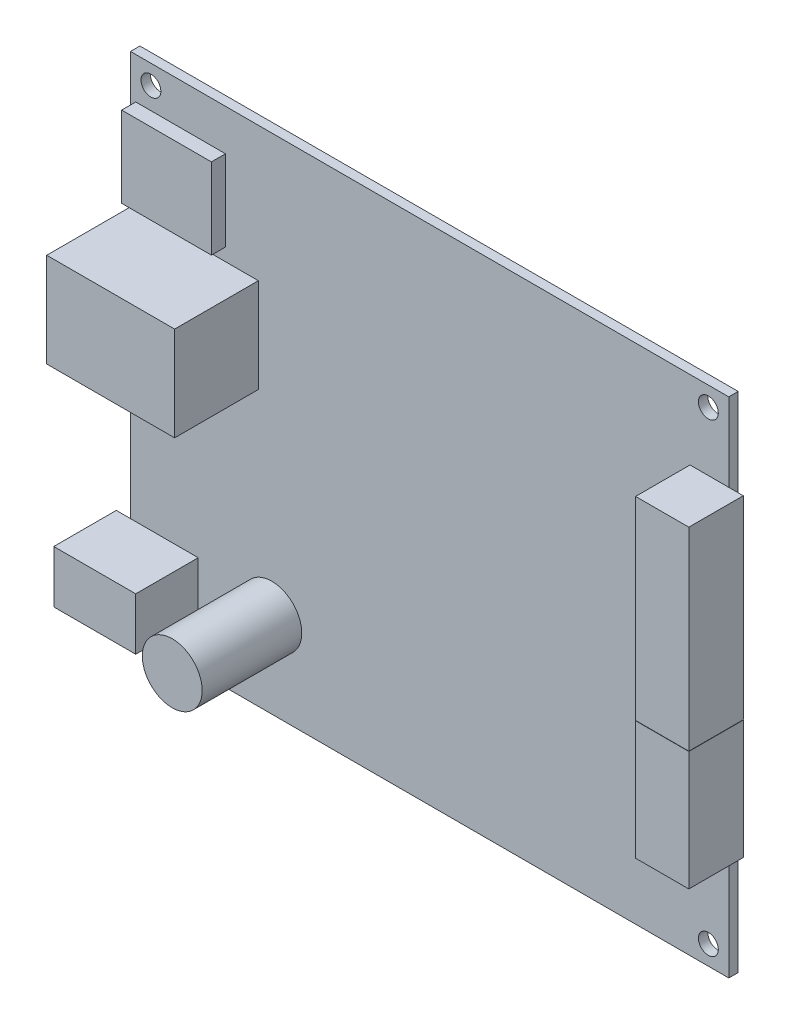
SolidWorks part; units mm, degrees
ref_plane "Front Plane" through (0, 0, 0) normal (0, 0, 1) x (1, 0, 0)
ref_plane "Top Plane" through (0, 0, 0) normal (0, 1, 0) x (1, 0, 0)
ref_plane "Right Plane" through (0, 0, 0) normal (1, 0, 0) x (0, 0, -1)
sketch "Sketch1" plane through (0, 0, 0) normal (0, 0, 1) x (1, 0, 0)
  line L1 (-50.8, -42.7355) -> (50.8, -42.7355)
  line L2 (-50.8, -42.7355) -> (-50.8, 42.7355)
  line L3 (-50.8, 42.7355) -> (50.8, 42.7355)
  line L4 (50.8, -42.7355) -> (50.8, 42.7355)
  line L5 (-50.8, -42.7355) -> (50.8, 42.7355) construction
  line L6 (-50.8, 42.7355) -> (50.8, -42.7355) construction
  point P0 (0, 0)
  dimension "D1" = 101.6
  dimension "D2" = 85.471
extrude "Boss-Extrude1" add sketch "Sketch1" along normal blind 1.6002
sketch "Sketch2" plane through (0, 0, 1.6002) normal (0, 0, 1) x (1, 0, 0)
  line L0 (-50.8, 42.7355) -> (-50.8, -42.7355) construction
  line L1 (-50.8, 3.8735) -> (-29.083, 3.8735)
  line L2 (-50.8, 3.8735) -> (-50.8, 19.8755)
  line L3 (-50.8, 19.8755) -> (-29.083, 19.8755)
  line L4 (-29.083, 3.8735) -> (-29.083, 19.8755)
  line L5 (50.8, 42.7355) -> (-50.8, 42.7355) construction
  dimension "D1" = 16.002
  dimension "D2" = 21.717
  dimension "D3" = 22.86
extrude "Ethernet" add sketch "Sketch2" along normal blind 14.224
sketch "Sketch3" plane through (0, 0, 1.6002) normal (0, 0, 1) x (1, 0, 0)
  line L1 (-53.213, -34.8615) -> (-39.2938, -34.8615)
  line L2 (-53.213, -34.8615) -> (-53.213, -25.9715)
  line L3 (-53.213, -25.9715) -> (-39.2938, -25.9715)
  line L4 (-39.2938, -34.8615) -> (-39.2938, -25.9715)
  line L5 (-50.8, -42.7355) -> (50.8, -42.7355) construction
  line L6 (-50.8, 3.8735) -> (-50.8, -42.7355) construction
  dimension "D1" = 8.89
  dimension "D2" = 13.9192
  dimension "D3" = 7.874
  dimension "D4" = 2.413
extrude "Power Connector" add sketch "Sketch3" along normal blind 10.6172
sketch "Sketch4" plane through (0, 0, 1.6002) normal (0, 0, 1) x (1, 0, 0)
  line L0 (50.8, 42.7355) -> (-50.8, 42.7355) construction
  line L1 (53.2638, 29.4259) -> (44.2214, 29.4259)
  line L2 (53.2638, 29.4259) -> (53.2638, -3.5179)
  line L3 (53.2638, -3.5179) -> (44.2214, -3.5179)
  line L4 (44.2214, 29.4259) -> (44.2214, -3.5179)
  line L5 (53.2638, -3.5687) -> (44.2214, -3.5687)
  line L6 (53.2638, -3.5687) -> (53.2638, -23.7871)
  line L7 (53.2638, -23.7871) -> (44.2214, -23.7871)
  line L8 (44.2214, -3.5687) -> (44.2214, -23.7871)
  line L9 (50.8, -42.7355) -> (50.8, 42.7355) construction
  dimension "D1" = 0.0508
  dimension "D2" = 9.0424
  dimension "D3" = 32.9438
  dimension "D4" = 20.2184
  dimension "D5" = 13.3096
  dimension "D6" = 2.4638
extrude "2x Connector" add sketch "Sketch4" along normal blind 9.2456
sketch "Sketch6" plane through (0, 0, 1.6002) normal (0, 0, 1) x (1, 0, 0)
  line L0 (-50.8, 42.7355) -> (-50.8, 19.8755) construction
  line L1 (-49.911, 22.0345) -> (-34.671, 22.0345)
  line L2 (-49.911, 22.0345) -> (-49.911, 35.7505)
  line L3 (-49.911, 35.7505) -> (-34.671, 35.7505)
  line L4 (-34.671, 22.0345) -> (-34.671, 35.7505)
  line L5 (50.8, 42.7355) -> (-50.8, 42.7355) construction
  dimension "D1" = 13.716
  dimension "D2" = 15.24
  dimension "D3" = 0.889
  dimension "D4" = 6.985
extrude "SD Card" add sketch "Sketch6" along normal blind 2.3876
sketch "Sketch7" plane through (0, 0, 1.6002) normal (0, 0, 1) x (1, 0, 0)
  line L0 (-50.8, -42.7355) -> (50.8, -42.7355) construction
  line L2 (50.8, -42.7355) -> (50.8, -23.7871) construction
  circle A0 centre (-26.797, -28.2575) radius 5.08
  dimension "D1" = 10.16
  dimension "D2" = 14.478
  dimension "D3" = 77.597
extrude "Capacator" add sketch "Sketch7" along normal blind 16.9164
sketch "Sketch5" plane through (0, 0, 0) normal (0, 0, -1) x (-1, 0, 0)
  line L0 (-50.8, -42.7355) -> (-50.8, 42.7355) construction
  line L1 (-50.8, 42.7355) -> (50.8, 42.7355) construction
  circle A0 centre (-47.3329, 39.4462) radius 1.6891
  dimension "D1" = 3.3782
  dimension "D2" = 3.4671
  dimension "D3" = 3.2893
extrude "Corner Hole" cut sketch "Sketch5" against normal through all
mirror "Mirror1" about plane through (0, 0, 0) normal (1, 0, 0) of "Corner Hole"
mirror "Mirror2" about plane through (0, 0, 0) normal (0, 1, 0) of "Mirror1", "Corner Hole"
